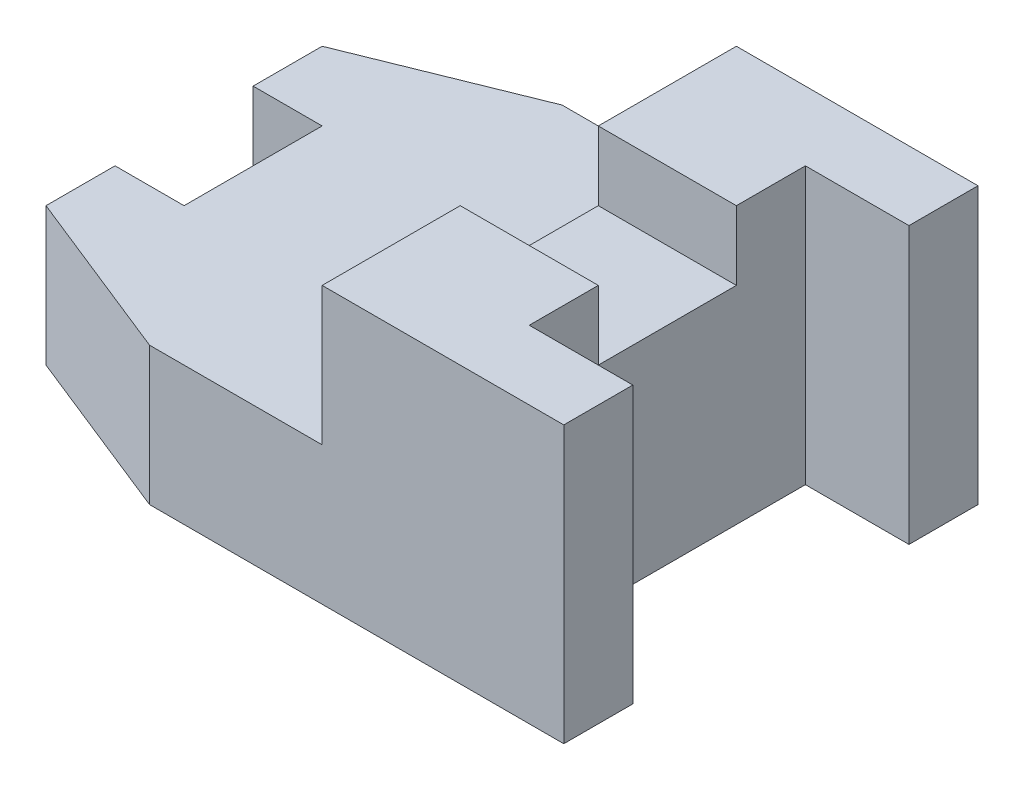
SolidWorks part; units mm, degrees
ref_plane "Front Plane" through (0, 0, 0) normal (0, 0, 1) x (1, 0, 0)
ref_plane "Top Plane" through (0, 0, 0) normal (0, 1, 0) x (1, 0, 0)
ref_plane "Right Plane" through (0, 0, 0) normal (1, 0, 0) x (0, 0, -1)
sketch "Sketch1" plane through (0, 0, 0) normal (0, 1, 0) x (1, 0, 0)
  line L1 (-42.5, -30) -> (42.5, -30)
  line L2 (-42.5, -30) -> (-42.5, 30)
  line L3 (-42.5, 30) -> (42.5, 30)
  line L4 (42.5, -30) -> (42.5, 30)
  line L5 (-42.5, -30) -> (42.5, 30) construction
  line L6 (-42.5, 30) -> (42.5, -30) construction
  point P0 (0, 0)
  dimension "D1" = 85
  dimension "D2" = 60
extrude "Boss-Extrude1" add sketch "Sketch1" along normal blind 40
sketch "Sketch2" plane through (0, 40, 0) normal (0, 1, 0) x (1, 0, 0)
  line L0 (42.5, -30) -> (42.5, 30) construction
  line L1 (42.5, 20) -> (27.5, 20)
  line L2 (42.5, 20) -> (42.5, -20)
  line L3 (42.5, -20) -> (27.5, -20)
  line L4 (27.5, 20) -> (27.5, -20)
  dimension "D1" = 40
  dimension "D2" = 15
  dimension "D3" = 10
extrude "Cut-Extrude1" cut sketch "Sketch2" against normal through all
sketch "Sketch3" plane through (0, 40, 0) normal (0, 1, 0) x (1, 0, 0)
  line L0 (27.5, 20) -> (27.5, -20) construction
  line L1 (27.5, 10) -> (7.5, 10)
  line L2 (27.5, 10) -> (27.5, -10)
  line L3 (27.5, -10) -> (7.5, -10)
  line L4 (7.5, 10) -> (7.5, -10)
  dimension "D1" = 20
  dimension "D2" = 20
  dimension "D3" = 10
extrude "Cut-Extrude2" cut sketch "Sketch3" against normal blind 10
sketch "Sketch4" plane through (0, 40, 0) normal (0, 1, 0) x (1, 0, 0)
  line L0 (7.5, 33.386) -> (7.5, -35.6918)
  line L1 (7.5, 10) -> (7.5, -10) construction
  dimension "D1" = 0
extrude "Cut-Extrude9" cut sketch "Sketch4" against normal blind 20 and the other way through all flip side to cut
sketch "Sketch6" plane through (-42.5, 0, 0) normal (-1, 0, 0) x (0, 0, 1)
  line L0 (-30, 20) -> (30, 20) construction
  line L1 (-10, 20) -> (10, 20)
  line L2 (-10, 20) -> (-10, 0)
  line L3 (-10, 0) -> (10, 0)
  line L4 (10, 20) -> (10, 0)
  line L5 (-30, 0) -> (30, 0) construction
  dimension "D1" = 20
  dimension "D2" = 10
extrude "Cut-Extrude10" cut sketch "Sketch6" against normal blind 10
sketch "Sketch9" plane through (0, 20, 0) normal (0, 1, 0) x (1, 0, 0)
  line L0 (-17.5, 33.415) -> (-17.5, -32.9193) construction
  line L1 (-50.7935, 20) -> (51.5366, 20) construction
  line L2 (-69.3472, -20) -> (47.09, -20) construction
  line L3 (-17.5, 30.1024) -> (-42.5, 20)
  line L6 (-42.5, -20) -> (-17.5, -30)
  dimension "D1" = 25
  dimension "D2" = 10
  dimension "D3" = 10
extrude "Cut-Extrude-Thin5" cut sketch "Sketch9" against normal through all thin
sketch "Sketch7" plane through (0, 20, 0) normal (0, 1, 0) x (1, 0, 0)
  line L0 (-17.5, 33.1939) -> (-17.5, -32.1371) construction
  line L1 (-47.4279, -20) -> (7.5, -20) construction
  line L2 (-45.0325, 20) -> (7.5, 20) construction
  line L3 (7.5, 10) -> (7.5, 30) construction
  line L4 (7.5, -30) -> (7.5, -10) construction
  line L5 (-17.5, -30) -> (-42.5, -20)
  line L6 (-42.2432, 20) -> (-5.1268, 30)
  line L7 (7.5, 30) -> (-17.7535, 30) construction
  dimension "D1" = 25
  dimension "D2" = 10
  dimension "D3" = 10
  dimension "D4" = 10.0033
  dimension "D5" = 10
